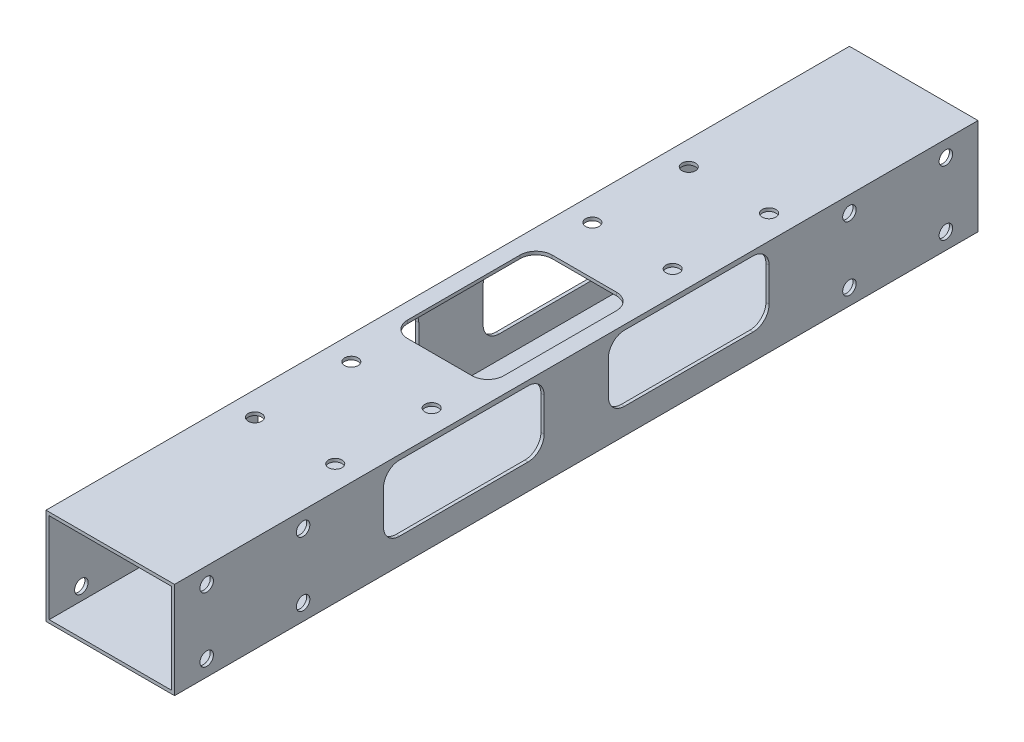
SolidWorks part; units mm, degrees
material "6061 合金"
ref_plane "前视基准面" through (0, 0, 0) normal (0, 0, 1) x (1, 0, 0)
ref_plane "上视基准面" through (0, 0, 0) normal (0, 1, 0) x (1, 0, 0)
ref_plane "右视基准面" through (0, 0, 0) normal (1, 0, 0) x (0, 0, -1)
other "Configuration Table"
sketch "草图1" plane through (0, 0, 0) normal (0, 0, 1) x (1, 0, 0)
  line L1 (-19, -14) -> (19, -14)
  line L2 (-19, -14) -> (-19, 14)
  line L3 (-19, 14) -> (19, 14)
  line L4 (19, -14) -> (19, 14)
  line L5 (-19, -14) -> (19, 14) construction
  line L6 (-19, 14) -> (19, -14) construction
  line L7 (-20, -15) -> (20, -15)
  line L8 (-20, -15) -> (-20, 15)
  line L9 (-20, 15) -> (20, 15)
  line L10 (20, -15) -> (20, 15)
  line L11 (-20, -15) -> (20, 15) construction
  line L12 (-20, 15) -> (20, -15) construction
  point P0 (0, 0)
  point P6 (0, 0)
  dimension "D1" = 1
  dimension "D2" = 1
  dimension "D3" = 40
  dimension "D4" = 30
extrude "凸台-拉伸1" add sketch "草图1" along normal blind 250
sketch "草图2" plane through (0, 0, 0) normal (1, 0, 0) x (0, 0, -1)
  line L0 (-250, 0) -> (0, 0) construction
  line L1 (-240, -10) -> (-210, -10) construction
  line L2 (-240, -10) -> (-240, 10) construction
  line L3 (-240, 10) -> (-210, 10) construction
  line L4 (-210, -10) -> (-210, 10) construction
  line L5 (-240, -10) -> (-210, 10) construction
  line L6 (-240, 10) -> (-210, -10) construction
  line L7 (-250, -15) -> (-250, 15) construction
  line L8 (-125, 15) -> (-125, -15) construction
  line L9 (-250, 15) -> (0, 15) construction
  line L10 (-250, -15) -> (0, -15) construction
  line L11 (-10, 10) -> (-40, -10) construction
  line L12 (-10, -10) -> (-40, 10) construction
  line L13 (-40, -10) -> (-40, 10) construction
  line L14 (-10, 10) -> (-40, 10) construction
  line L15 (-10, -10) -> (-10, 10) construction
  line L16 (-10, -10) -> (-40, -10) construction
  circle A0 centre (-210, 10) radius 2.1
  circle A1 centre (-240, 10) radius 2.1
  circle A2 centre (-210, -10) radius 2.1
  circle A3 centre (-240, -10) radius 2.1
  circle A4 centre (-10, -10) radius 2.1
  circle A5 centre (-40, -10) radius 2.1
  circle A6 centre (-10, 10) radius 2.1
  circle A7 centre (-40, 10) radius 2.1
  point P0 (-225, 0)
  point P28 (-25, 0)
  dimension "D1" = 4.2
  dimension "D2" = 4.2
  dimension "D3" = 170
  dimension "D4" = 20
  dimension "D5" = 30
extrude "切除-拉伸1" cut sketch "草图2" against normal through all and the other way through all
sketch "草图3" plane through (0, 0, 0) normal (0, 1, 0) x (1, 0, 0)
  line L0 (-20, -125) -> (20, -125) construction
  line L1 (-20, -250) -> (-20, 0) construction
  line L2 (20, -250) -> (20, 0) construction
  line L3 (-12.5, -162.5) -> (12.5, -192.5) construction
  line L4 (-12.5, -57.5) -> (12.5, -57.5) construction
  line L5 (-12.5, -57.5) -> (-12.5, -87.5) construction
  line L6 (-12.5, -87.5) -> (12.5, -87.5) construction
  line L7 (12.5, -57.5) -> (12.5, -87.5) construction
  line L8 (-12.5, -57.5) -> (12.5, -87.5) construction
  line L9 (-12.5, -87.5) -> (12.5, -57.5) construction
  line L10 (-12.5, -192.5) -> (12.5, -162.5) construction
  line L11 (12.5, -192.5) -> (12.5, -162.5) construction
  line L12 (-12.5, -162.5) -> (12.5, -162.5) construction
  line L13 (-12.5, -192.5) -> (-12.5, -162.5) construction
  line L14 (-12.5, -192.5) -> (12.5, -192.5) construction
  line L16 (-10, -147.5) -> (10, -147.5)
  line L17 (-15, -142.5) -> (-15, -107.5)
  line L18 (-10, -102.5) -> (10, -102.5)
  line L19 (15, -142.5) -> (15, -107.5)
  line L20 (-15, -147.5) -> (15, -102.5) construction
  line L21 (-15, -102.5) -> (15, -147.5) construction
  circle A0 centre (-12.5, -87.5) radius 2.1
  circle A1 centre (12.5, -87.5) radius 2.1
  circle A2 centre (-12.5, -57.5) radius 2.1
  circle A3 centre (12.5, -57.5) radius 2.1
  circle A4 centre (12.5, -192.5) radius 2.1
  circle A5 centre (-12.5, -192.5) radius 2.1
  circle A6 centre (12.5, -162.5) radius 2.1
  circle A7 centre (-12.5, -162.5) radius 2.1
  arc A8 (-10, -147.5) -> (-15, -142.5) centre (-10, -142.5) cw
  arc A9 (10, -147.5) -> (15, -142.5) centre (10, -142.5) ccw
  arc A10 (10, -102.5) -> (15, -107.5) centre (10, -107.5) cw
  arc A11 (-15, -107.5) -> (-10, -102.5) centre (-10, -107.5) cw
  point P6 (0, -72.5)
  point P14 (0, -125)
  point P27 (0, -177.5)
  dimension "D2" = 4.2
  dimension "D3" = 4.2
  dimension "D7" = 5
  dimension "D4" = 25
  dimension "D5" = 30
  dimension "D6" = 75
  dimension "D8" = 5
  dimension "D9" = 15
  dimension "D1" = 2
extrude "切除-拉伸2" cut sketch "草图3" against normal up to next (14 mm away) from surface at 15 starting at face at (0, 15, 125)
sketch "草图4" plane through (0, 0, 0) normal (1, 0, 0) x (0, 0, -1)
  line L0 (-250, 15) -> (0, 15) construction
  line L1 (-180, -7) -> (-140, -7)
  line L2 (-185, -2) -> (-185, 8.5)
  line L3 (-180, 13.5) -> (-140, 13.5)
  line L4 (-135, -2) -> (-135, 8.5)
  line L5 (-185, -7) -> (-135, 13.5) construction
  line L6 (-185, 13.5) -> (-135, -7) construction
  line L7 (-250, -15) -> (0, -15) construction
  line L9 (-125, 15) -> (-125, -15) construction
  line L10 (-65, 13.5) -> (-115, -7) construction
  line L11 (-65, -7) -> (-115, 13.5) construction
  line L12 (-115, -2) -> (-115, 8.5)
  line L13 (-70, 13.5) -> (-110, 13.5)
  line L14 (-65, -2) -> (-65, 8.5)
  line L15 (-70, -7) -> (-110, -7)
  arc A0 (-140, 13.5) -> (-135, 8.5) centre (-140, 8.5) cw
  arc A1 (-140, -7) -> (-135, -2) centre (-140, -2) ccw
  arc A2 (-180, -7) -> (-185, -2) centre (-180, -2) cw
  arc A3 (-185, 8.5) -> (-180, 13.5) centre (-180, 8.5) cw
  circle A4 centre (-210, 10) radius 2.1 construction
  arc A5 (-65, 8.5) -> (-70, 13.5) centre (-70, 8.5) ccw
  arc A6 (-70, -7) -> (-65, -2) centre (-70, -2) ccw
  arc A7 (-110, -7) -> (-115, -2) centre (-110, -2) cw
  arc A8 (-110, 13.5) -> (-115, 8.5) centre (-110, 8.5) ccw
  point P0 (-160, 3.25)
  point P42 (-90, 3.25)
  dimension "D1" = 5
  dimension "D2" = 1.5
  dimension "D3" = 8
  dimension "D4" = 50
  dimension "D5" = 25
extrude "切除-拉伸3" cut sketch "草图4" against normal through all and the other way through all
